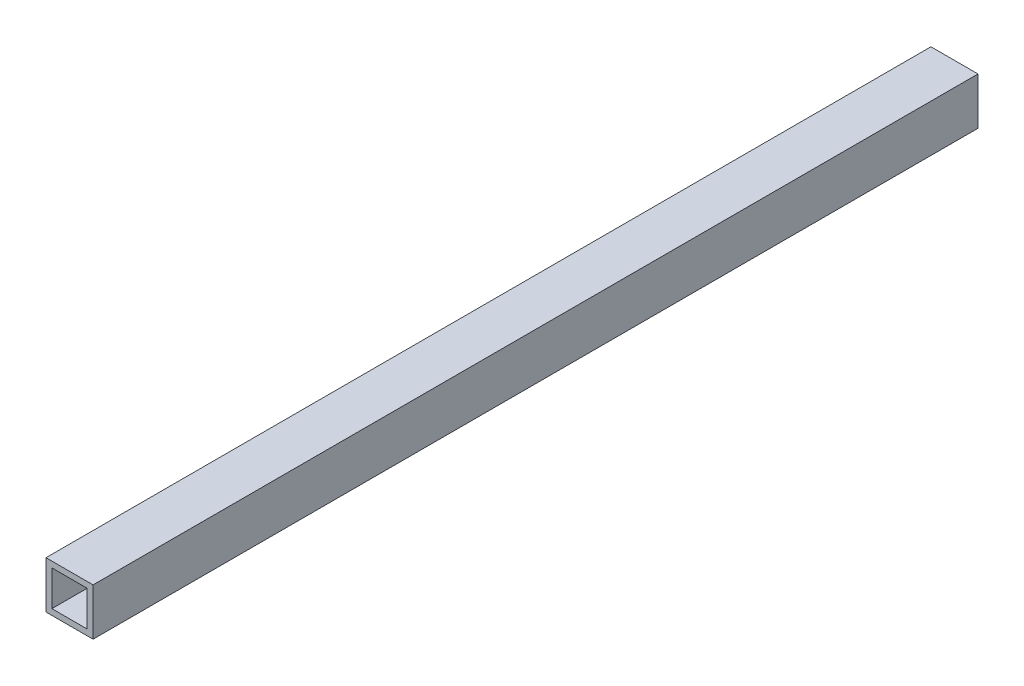
SolidWorks part; units mm, degrees
ref_plane "Front Plane" through (0, 0, 0) normal (0, 0, 1) x (1, 0, 0)
ref_plane "Top Plane" through (0, 0, 0) normal (0, 1, 0) x (1, 0, 0)
ref_plane "Right Plane" through (0, 0, 0) normal (1, 0, 0) x (0, 0, -1)
sketch "Sketch1" plane through (0, 0, 0) normal (0, 0, 1) x (1, 0, 0)
  line L0 (12.7, 0) -> (9.525, 0) construction
  line L1 (-12.7, 0) -> (12.7, 0) construction
  line L2 (0, 12.7) -> (0, -12.7)
  point P7 (0, 0)
sketch "Sketch2" plane through (0, 0, 0) normal (1, 0, 0) x (0, 0, -1)
  line L0 (238.76, 0) -> (-238.76, 0)
  point P4 (0, 0)
  dimension "Length" = 477.52
sketch "Sketch3" plane through (0, 0, 0) normal (0, 0, 1) x (1, 0, 0)
  line L0 (-12.7, 0) -> (12.7, 0) construction
  line L5 (12.7, -12.7) -> (-12.7, -12.7)
  line L6 (12.7, -12.7) -> (12.7, 12.7)
  line L11 (12.7, 12.7) -> (-12.7, 12.7)
  line L12 (-12.7, -12.7) -> (-12.7, 12.7)
  line L14 (12.7, -12.7) -> (-12.7, 12.7) construction
  line L15 (12.7, 12.7) -> (-12.7, -12.7) construction
  line L16 (9.525, -9.525) -> (-9.525, -9.525)
  line L17 (9.525, -9.525) -> (9.525, 9.525)
  line L18 (9.525, 9.525) -> (-9.525, 9.525)
  line L19 (-9.525, -9.525) -> (-9.525, 9.525)
  line L20 (9.525, -9.525) -> (-9.525, 9.525) construction
  line L21 (9.525, 9.525) -> (-9.525, -9.525) construction
  point P0 (0, 0)
  point P5 (0, 0)
  point P13 (9.525, -12.7)
  dimension "D1" = 3.175
  dimension "D3" = 25.4
  dimension "D4" = 25.4
extrude "Boss-Extrude1" add sketch "Sketch3" along normal up to vertex (238.76 mm away) and the other way up to vertex (238.76 mm away) up to point (0, 0, 238.76) other way up to point (0, 0, -238.76)
sketch "Sketch5" plane through (0, 0, 0) normal (1, 0, 0) x (0, 0, -1)
  line L0 (-238.76, 0) -> (238.76, 0) construction
  line L3 (-238.76, -12.7) -> (-238.76, 12.7) construction
  line L4 (238.76, -12.7) -> (238.76, 12.7) construction
  point P6 (-210.185, 0)
  point P7 (-200.66, 0)
  point P8 (200.66, 0)
  point P10 (210.185, 0)
  dimension "D1" = 28.575
  dimension "D2" = 38.1
  dimension "D3" = 28.575
  dimension "D4" = 38.1
equation "\"D1@Sketch3\"=\"Wall thickness@Sketch1\""
equation "\"D1@Sketch5\"=\"Width@Sketch1\"*1.125"
equation "\"D2@Sketch5\"=\"Width@Sketch1\"*1.5"
equation "\"D3@Sketch5\"=\"D1@Sketch5\""
equation "\"D4@Sketch5\"=\"D2@Sketch5\""
equation "\"D2@Sketch3\"=\"Wall Thickness@Sketch1\""
